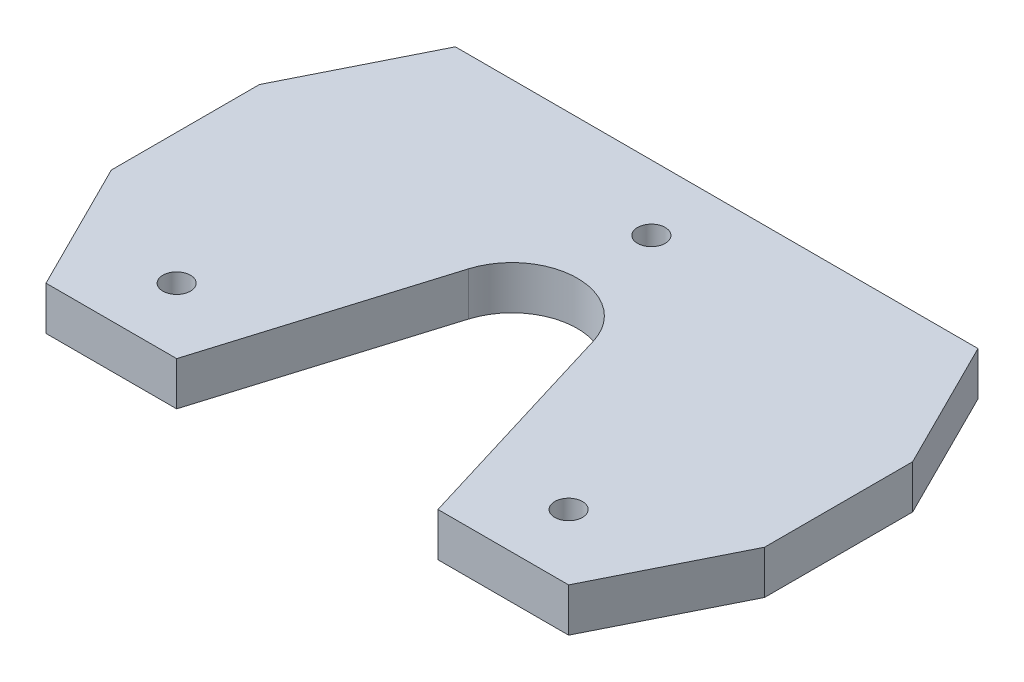
SolidWorks part; units mm, degrees
ref_plane "Front" through (0, 0, 0) normal (0, 0, 1) x (1, 0, 0)
ref_plane "Top" through (0, 0, 0) normal (0, 1, 0) x (1, 0, 0)
ref_plane "Right" through (0, 0, 0) normal (1, 0, 0) x (0, 0, -1)
sketch "Sketch1" plane through (0, 0, 0) normal (0, 1, 0) x (1, 0, 0)
  line L0 (-60, 27.301) -> (60, 27.301)
  line L1 (-60, 27.301) -> (-75, -2.699)
  line L2 (-75, -2.699) -> (-75, -36.699)
  line L3 (-75, -36.699) -> (-60, -66.699)
  line L4 (-60, -66.699) -> (-30, -66.699)
  line L6 (-30, -66.699) -> (-14.349, -15.3275)
  line L7 (60, 27.301) -> (75, -2.699)
  line L8 (75, -2.699) -> (75, -36.699)
  line L9 (75, -36.699) -> (60, -66.699)
  line L10 (60, -66.699) -> (30, -66.699)
  line L12 (30, -66.699) -> (14.3487, -15.3274)
  arc A0 (14.3487, -15.3274) -> (-14.349, -15.3275) centre (-0.0002, -19.699) ccw
  circle A1 centre (-45, -51.699) radius 3.175
  circle A2 centre (0, 12.301) radius 3.175
  circle A3 centre (45, -51.699) radius 3.175
  dimension "D19" = 6.35
  dimension "D20" = 6.35
  dimension "D21" = 6.35
  dimension "D23" = 15
  dimension "D1" = 120
  dimension "D2" = 34
  dimension "D3" = 15
  dimension "D4" = 15
  dimension "D5" = 15
  dimension "D6" = 30
  dimension "D7" = 15
  dimension "D8" = 30
  dimension "D9" = 34
  dimension "D10" = 30
  dimension "D11" = 30
  dimension "D12" = 30
  dimension "D13" = 30
  dimension "D14" = 15
  dimension "D15" = 15
  dimension "D16" = 15
  dimension "D17" = 15
  dimension "D18" = 15
  dimension "D22" = 47
extrude "Boss-Extrude1" add sketch "Sketch1" along normal blind 10
